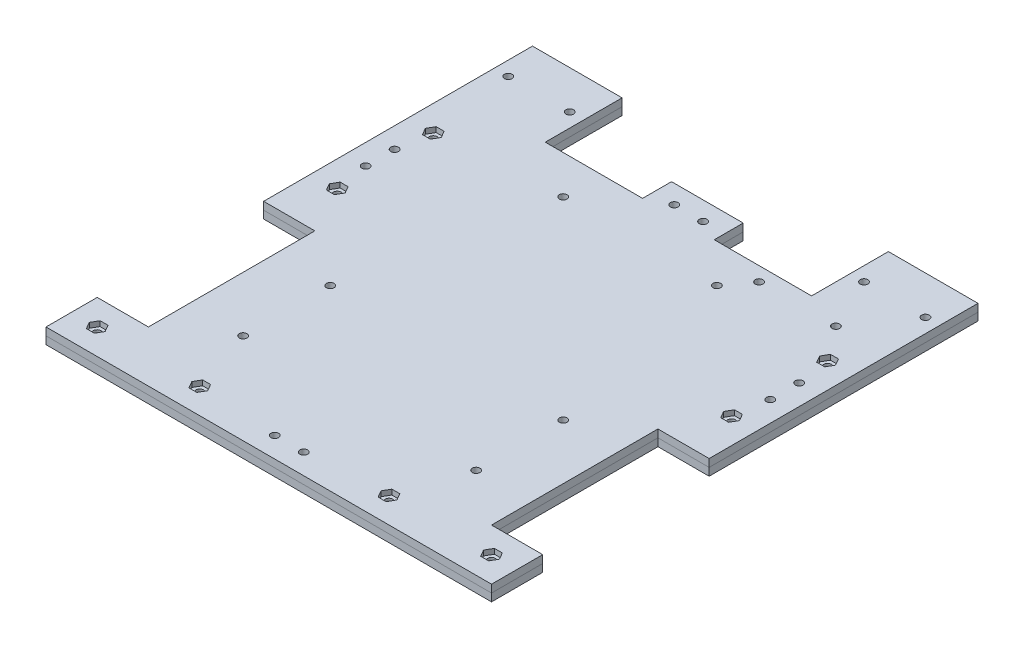
SolidWorks part; units mm, degrees
ref_plane "Alzado" through (0, 0, 0) normal (0, 0, 1) x (1, 0, 0)
ref_plane "Planta" through (0, 0, 0) normal (0, 1, 0) x (1, 0, 0)
ref_plane "Vista lateral" through (0, 0, 0) normal (1, 0, 0) x (0, 0, -1)
sketch "Croquis1" plane through (0, 0, 0) normal (0, 1, 0) x (1, 0, 0)
  line L0 (87, -80) -> (87, -60)
  line L1 (-87, 80) -> (87, 80)
  line L2 (-87, 80) -> (-87, -80)
  line L3 (-87, -80) -> (87, -80)
  line L4 (87, 80) -> (87, -80)
  line L5 (-87, 80) -> (87, -80) construction
  line L6 (-87, -80) -> (87, 80) construction
  line L7 (87, -60) -> (67, -60)
  line L8 (67, -60) -> (67, 5)
  line L9 (67, 5) -> (87, 5)
  line L10 (87, 80) -> (87, 110)
  line L11 (87, 110) -> (52, 110)
  line L12 (52, 110) -> (52, 80)
  line L13 (0, 0) -> (0, -80) construction
  line L14 (-87, -60) -> (-67, -60)
  line L15 (-67, -60) -> (-67, 5)
  line L16 (-67, 5) -> (-87, 5)
  line L17 (-87, 80) -> (-87, 110)
  line L18 (-87, 110) -> (-52, 110)
  line L19 (-52, 110) -> (-52, 80)
  point P0 (0, 0)
  dimension "D1" = 160
  dimension "D2" = 174
  dimension "D3" = 20
  dimension "D4" = 20
  dimension "D5" = 65
  dimension "D6" = 30
  dimension "D7" = 35
extrude "Saliente-Extruir1" add sketch "Croquis1" along normal blind 7 contours L16 L15 L14 L2 L3 L0 L7 L8 L9 L4 L1 | L11 L12 L1 L10 | L19 L18 L17 L1
sketch "Croquis3" plane through (0, 7, 0) normal (0, 1, 0) x (1, 0, 0)
  line L0 (-87, -60) -> (-87, -80) construction
  line L1 (-87, -60) -> (-67, -60) construction
  line L2 (-87, -80) -> (87, -80) construction
  line L3 (-87, -60) -> (-87, -80) construction
  line L4 (-87, -80) -> (-87, -60) construction
  line L5 (-87, -60) -> (-67, -60) construction
  line L6 (-67, -60) -> (-77, -60) construction
  line L7 (-77, -60) -> (-87, -60) construction
  line L8 (-87, -60) -> (-87, -80) construction
  line L9 (-87, -80) -> (-87, -70) construction
  line L10 (-87, 5) -> (-67, 5) construction
  line L11 (-80.1, -70) -> (-78.55, -72.6847)
  line L12 (-78.55, -72.6847) -> (-75.45, -72.6847)
  line L13 (-75.45, -72.6847) -> (-73.9, -70)
  line L14 (-73.9, -70) -> (-75.45, -67.3153)
  line L15 (-75.45, -67.3153) -> (-78.55, -67.3153)
  line L16 (-78.55, -67.3153) -> (-80.1, -70)
  line L17 (-87, 110) -> (-87, 5) construction
  line L18 (-67, 5) -> (-87, 5) construction
  line L19 (-67, -60) -> (-67, 5) construction
  line L20 (-67, 5) -> (-77, 5) construction
  line L21 (-52, 110) -> (-52, 80) construction
  line L22 (-52, 110) -> (-52, 80) construction
  line L23 (-52, 80) -> (-87, 80) construction
  line L24 (-87, 80) -> (-69.5, 80) construction
  line L25 (-67, 5) -> (-67, 80) construction
  line L26 (-67, 80) -> (-77, 80) construction
  line L27 (-77, 80) -> (-77, 5) construction
  line L28 (-77, 5) -> (-77, 80) construction
  line L29 (-77, 80) -> (-77, 42.5) construction
  line L30 (-77, 42.5) -> (-77, 5) construction
  line L31 (-77, 5) -> (-77, 23.75) construction
  line L32 (-77, 23.75) -> (-77, 42.5) construction
  line L33 (-77, 42.5) -> (-77, 61.25) construction
  line L34 (0, 0) -> (0, -80) construction
  line L35 (-80.1, 61.25) -> (-78.55, 58.5653)
  line L36 (-78.55, 58.5653) -> (-75.45, 58.5653)
  line L37 (-75.45, 58.5653) -> (-73.9, 61.25)
  line L38 (-73.9, 61.25) -> (-75.45, 63.9347)
  line L39 (-75.45, 63.9347) -> (-78.55, 63.9347)
  line L40 (-78.55, 63.9347) -> (-80.1, 61.25)
  line L41 (-73.9, 23.75) -> (-75.45, 26.4347)
  line L42 (-75.45, 26.4347) -> (-78.55, 26.4347)
  line L43 (-78.55, 26.4347) -> (-80.1, 23.75)
  line L44 (-80.1, 23.75) -> (-78.55, 21.0653)
  line L45 (-78.55, 21.0653) -> (-75.45, 21.0653)
  line L46 (-75.45, 21.0653) -> (-73.9, 23.75)
  line L47 (78.55, 63.9347) -> (80.1, 61.25)
  line L48 (75.45, 63.9347) -> (78.55, 63.9347)
  line L49 (73.9, 61.25) -> (75.45, 63.9347)
  line L50 (75.45, 58.5653) -> (73.9, 61.25)
  line L51 (78.55, 58.5653) -> (75.45, 58.5653)
  line L52 (80.1, 61.25) -> (78.55, 58.5653)
  line L53 (75.45, 21.0653) -> (73.9, 23.75)
  line L54 (78.55, 21.0653) -> (75.45, 21.0653)
  line L55 (80.1, 23.75) -> (78.55, 21.0653)
  line L56 (78.55, 26.4347) -> (80.1, 23.75)
  line L57 (75.45, 26.4347) -> (78.55, 26.4347)
  line L58 (73.9, 23.75) -> (75.45, 26.4347)
  line L59 (78.55, -67.3153) -> (80.1, -70)
  line L60 (75.45, -67.3153) -> (78.55, -67.3153)
  line L61 (73.9, -70) -> (75.45, -67.3153)
  line L62 (75.45, -72.6847) -> (73.9, -70)
  line L63 (78.55, -72.6847) -> (75.45, -72.6847)
  line L64 (80.1, -70) -> (78.55, -72.6847)
  circle A0 centre (-77, -70) radius 3.1 construction
  circle A1 centre (-77, 61.25) radius 3.1 construction
  circle A2 centre (-77, 23.75) radius 3.1 construction
extrude "Cortar-Extruir1" cut sketch "Croquis3" against normal blind 2
sketch "Croquis4" plane through (0, 0, 0) normal (0, -1, 0) x (1, 0, 0)
  line L0 (-78.55, 67.3153) -> (-80.1, 70) construction
  line L1 (-80.1, 70) -> (-78.55, 72.6847) construction
  line L2 (-78.55, 72.6847) -> (-75.45, 72.6847) construction
  line L3 (-75.45, 72.6847) -> (-73.9, 70) construction
  line L4 (-73.9, 70) -> (-75.45, 67.3153) construction
  line L5 (-75.45, 67.3153) -> (-78.55, 67.3153) construction
  line L6 (-75.45, -21.0653) -> (-73.9, -23.75) construction
  line L7 (-73.9, -23.75) -> (-75.45, -26.4347) construction
  line L8 (-75.45, -26.4347) -> (-78.55, -26.4347) construction
  line L9 (-78.55, -26.4347) -> (-80.1, -23.75) construction
  line L10 (-80.1, -23.75) -> (-78.55, -21.0653) construction
  line L11 (-78.55, -21.0653) -> (-75.45, -21.0653) construction
  line L12 (-78.55, -63.9347) -> (-80.1, -61.25) construction
  line L13 (-80.1, -61.25) -> (-78.55, -58.5653) construction
  line L14 (-78.55, -58.5653) -> (-75.45, -58.5653) construction
  line L15 (-75.45, -58.5653) -> (-73.9, -61.25) construction
  line L16 (-73.9, -61.25) -> (-75.45, -63.9347) construction
  line L17 (-75.45, -63.9347) -> (-78.55, -63.9347) construction
  line L18 (78.55, -63.9347) -> (75.45, -63.9347) construction
  line L19 (75.45, -63.9347) -> (73.9, -61.25) construction
  line L20 (73.9, -61.25) -> (75.45, -58.5653) construction
  line L21 (75.45, -58.5653) -> (78.55, -58.5653) construction
  line L22 (78.55, -58.5653) -> (80.1, -61.25) construction
  line L23 (80.1, -61.25) -> (78.55, -63.9347) construction
  line L24 (75.45, -21.0653) -> (78.55, -21.0653) construction
  line L25 (78.55, -21.0653) -> (80.1, -23.75) construction
  line L26 (80.1, -23.75) -> (78.55, -26.4347) construction
  line L27 (78.55, -26.4347) -> (75.45, -26.4347) construction
  line L28 (75.45, -26.4347) -> (73.9, -23.75) construction
  line L29 (73.9, -23.75) -> (75.45, -21.0653) construction
  line L30 (78.55, 67.3153) -> (75.45, 67.3153) construction
  line L31 (75.45, 67.3153) -> (73.9, 70) construction
  line L32 (73.9, 70) -> (75.45, 72.6847) construction
  line L33 (75.45, 72.6847) -> (78.55, 72.6847) construction
  line L34 (78.55, 72.6847) -> (80.1, 70) construction
  line L35 (80.1, 70) -> (78.55, 67.3153) construction
  line L36 (-78.55, 67.3153) -> (-80.1, 70)
  line L37 (-80.1, 70) -> (-78.55, 72.6847)
  line L38 (-78.55, 72.6847) -> (-75.45, 72.6847)
  line L39 (-75.45, 72.6847) -> (-73.9, 70)
  line L40 (-73.9, 70) -> (-75.45, 67.3153)
  line L41 (-75.45, 67.3153) -> (-78.55, 67.3153)
  line L42 (-75.45, -21.0653) -> (-73.9, -23.75)
  line L43 (-73.9, -23.75) -> (-75.45, -26.4347)
  line L44 (-75.45, -26.4347) -> (-78.55, -26.4347)
  line L45 (-78.55, -26.4347) -> (-80.1, -23.75)
  line L46 (-80.1, -23.75) -> (-78.55, -21.0653)
  line L47 (-78.55, -21.0653) -> (-75.45, -21.0653)
  line L48 (-78.55, -63.9347) -> (-80.1, -61.25)
  line L49 (-80.1, -61.25) -> (-78.55, -58.5653)
  line L50 (-78.55, -58.5653) -> (-75.45, -58.5653)
  line L51 (-75.45, -58.5653) -> (-73.9, -61.25)
  line L52 (-73.9, -61.25) -> (-75.45, -63.9347)
  line L53 (-75.45, -63.9347) -> (-78.55, -63.9347)
  line L54 (78.55, -63.9347) -> (75.45, -63.9347)
  line L55 (75.45, -63.9347) -> (73.9, -61.25)
  line L56 (73.9, -61.25) -> (75.45, -58.5653)
  line L57 (75.45, -58.5653) -> (78.55, -58.5653)
  line L58 (78.55, -58.5653) -> (80.1, -61.25)
  line L59 (80.1, -61.25) -> (78.55, -63.9347)
  line L60 (75.45, -21.0653) -> (78.55, -21.0653)
  line L61 (78.55, -21.0653) -> (80.1, -23.75)
  line L62 (80.1, -23.75) -> (78.55, -26.4347)
  line L63 (78.55, -26.4347) -> (75.45, -26.4347)
  line L64 (75.45, -26.4347) -> (73.9, -23.75)
  line L65 (73.9, -23.75) -> (75.45, -21.0653)
  line L66 (78.55, 67.3153) -> (75.45, 67.3153)
  line L67 (75.45, 67.3153) -> (73.9, 70)
  line L68 (73.9, 70) -> (75.45, 72.6847)
  line L69 (75.45, 72.6847) -> (78.55, 72.6847)
  line L70 (78.55, 72.6847) -> (80.1, 70)
  line L71 (80.1, 70) -> (78.55, 67.3153)
  line L72 (-73.9, 70) -> (-80.1, 70) construction
  line L73 (-80.1, 70) -> (-77, 70) construction
  line L74 (-77, 70) -> (80.1, 70) construction
  line L75 (73.9, 70) -> (80.1, 70) construction
  line L76 (77, 70) -> (73.9, 70) construction
  line L77 (73.9, 70) -> (-73.9, 70) construction
  line L78 (-73.9, 70) -> (73.9, 70) construction
  line L79 (0, 0) -> (0, 70) construction
  line L80 (0, 70) -> (73.9, 70) construction
  line L81 (0, 70) -> (-73.9, 70) construction
  line L82 (-36.95, 70) -> (0, 70) construction
  line L83 (0, 70) -> (73.9, 70) construction
  line L84 (36.95, 70) -> (73.9, 70) construction
  line L92 (40.05, 70) -> (38.5, 72.6847)
  line L93 (38.5, 72.6847) -> (35.4, 72.6847)
  line L94 (35.4, 72.6847) -> (33.85, 70)
  line L95 (33.85, 70) -> (35.4, 67.3153)
  line L96 (35.4, 67.3153) -> (38.5, 67.3153)
  line L97 (38.5, 67.3153) -> (40.05, 70)
  line L98 (-33.85, 70) -> (-35.4, 72.6847)
  line L99 (-35.4, 72.6847) -> (-38.5, 72.6847)
  line L100 (-38.5, 72.6847) -> (-40.05, 70)
  line L101 (-40.05, 70) -> (-38.5, 67.3153)
  line L102 (-38.5, 67.3153) -> (-35.4, 67.3153)
  line L103 (-35.4, 67.3153) -> (-33.85, 70)
  circle A0 centre (-36.95, 70) radius 3.1 construction
  circle A1 centre (36.95, 70) radius 3.1 construction
extrude "Cortar-Extruir2" cut sketch "Croquis4" against normal blind 2
sketch "Croquis5" plane through (0, 7, 0) normal (0, 1, 0) x (1, 0, 0)
  line L0 (78.55, -67.3153) -> (75.45, -67.3153) construction
  line L1 (75.45, -67.3153) -> (73.9, -70) construction
  line L2 (73.9, -70) -> (75.45, -72.6847) construction
  line L3 (75.45, -72.6847) -> (78.55, -72.6847) construction
  line L4 (78.55, -72.6847) -> (80.1, -70) construction
  line L5 (80.1, -70) -> (78.55, -67.3153) construction
  line L6 (-78.55, -67.3153) -> (-80.1, -70) construction
  line L7 (-80.1, -70) -> (-78.55, -72.6847) construction
  line L8 (-78.55, -72.6847) -> (-75.45, -72.6847) construction
  line L9 (-75.45, -72.6847) -> (-73.9, -70) construction
  line L10 (-73.9, -70) -> (-75.45, -67.3153) construction
  line L11 (-75.45, -67.3153) -> (-78.55, -67.3153) construction
  line L12 (-75.45, 21.0653) -> (-73.9, 23.75) construction
  line L13 (-73.9, 23.75) -> (-75.45, 26.4347) construction
  line L14 (-75.45, 26.4347) -> (-78.55, 26.4347) construction
  line L15 (-78.55, 26.4347) -> (-80.1, 23.75) construction
  line L16 (-80.1, 23.75) -> (-78.55, 21.0653) construction
  line L17 (-78.55, 21.0653) -> (-75.45, 21.0653) construction
  line L18 (75.45, 21.0653) -> (78.55, 21.0653) construction
  line L19 (78.55, 21.0653) -> (80.1, 23.75) construction
  line L20 (80.1, 23.75) -> (78.55, 26.4347) construction
  line L21 (78.55, 26.4347) -> (75.45, 26.4347) construction
  line L22 (75.45, 26.4347) -> (73.9, 23.75) construction
  line L23 (73.9, 23.75) -> (75.45, 21.0653) construction
  line L24 (78.55, 63.9347) -> (75.45, 63.9347) construction
  line L25 (75.45, 63.9347) -> (73.9, 61.25) construction
  line L26 (73.9, 61.25) -> (75.45, 58.5653) construction
  line L27 (75.45, 58.5653) -> (78.55, 58.5653) construction
  line L28 (78.55, 58.5653) -> (80.1, 61.25) construction
  line L29 (80.1, 61.25) -> (78.55, 63.9347) construction
  line L30 (-78.55, 63.9347) -> (-80.1, 61.25) construction
  line L31 (-80.1, 61.25) -> (-78.55, 58.5653) construction
  line L32 (-78.55, 58.5653) -> (-75.45, 58.5653) construction
  line L33 (-75.45, 58.5653) -> (-73.9, 61.25) construction
  line L34 (-73.9, 61.25) -> (-75.45, 63.9347) construction
  line L35 (-75.45, 63.9347) -> (-78.55, 63.9347) construction
  line L36 (78.55, -67.3153) -> (75.45, -67.3153)
  line L37 (75.45, -67.3153) -> (73.9, -70)
  line L38 (73.9, -70) -> (75.45, -72.6847)
  line L39 (75.45, -72.6847) -> (78.55, -72.6847)
  line L40 (78.55, -72.6847) -> (80.1, -70)
  line L41 (80.1, -70) -> (78.55, -67.3153)
  line L42 (-78.55, -67.3153) -> (-80.1, -70)
  line L43 (-80.1, -70) -> (-78.55, -72.6847)
  line L44 (-78.55, -72.6847) -> (-75.45, -72.6847)
  line L45 (-75.45, -72.6847) -> (-73.9, -70)
  line L46 (-73.9, -70) -> (-75.45, -67.3153)
  line L47 (-75.45, -67.3153) -> (-78.55, -67.3153)
  line L48 (-75.45, 21.0653) -> (-73.9, 23.75)
  line L49 (-73.9, 23.75) -> (-75.45, 26.4347)
  line L50 (-75.45, 26.4347) -> (-78.55, 26.4347)
  line L51 (-78.55, 26.4347) -> (-80.1, 23.75)
  line L52 (-80.1, 23.75) -> (-78.55, 21.0653)
  line L53 (-78.55, 21.0653) -> (-75.45, 21.0653)
  line L54 (75.45, 21.0653) -> (78.55, 21.0653)
  line L55 (78.55, 21.0653) -> (80.1, 23.75)
  line L56 (80.1, 23.75) -> (78.55, 26.4347)
  line L57 (78.55, 26.4347) -> (75.45, 26.4347)
  line L58 (75.45, 26.4347) -> (73.9, 23.75)
  line L59 (73.9, 23.75) -> (75.45, 21.0653)
  line L60 (78.55, 63.9347) -> (75.45, 63.9347)
  line L61 (75.45, 63.9347) -> (73.9, 61.25)
  line L62 (73.9, 61.25) -> (75.45, 58.5653)
  line L63 (75.45, 58.5653) -> (78.55, 58.5653)
  line L64 (78.55, 58.5653) -> (80.1, 61.25)
  line L65 (80.1, 61.25) -> (78.55, 63.9347)
  line L66 (-78.55, 63.9347) -> (-80.1, 61.25)
  line L67 (-80.1, 61.25) -> (-78.55, 58.5653)
  line L68 (-78.55, 58.5653) -> (-75.45, 58.5653)
  line L69 (-75.45, 58.5653) -> (-73.9, 61.25)
  line L70 (-73.9, 61.25) -> (-75.45, 63.9347)
  line L71 (-75.45, 63.9347) -> (-78.55, 63.9347)
  line L72 (-77, 58.5653) -> (-77, 61.25) construction
  line L73 (-77, 21.0653) -> (-77, 23.75) construction
  line L74 (-77, -72.6847) -> (-77, -70) construction
  line L75 (0, 0) -> (0, -80) construction
  line L76 (-87, -80) -> (87, -80) construction
  circle A0 centre (-77, -70) radius 1.5
  circle A1 centre (-77, 23.75) radius 1.5
  circle A2 centre (-77, 61.25) radius 1.5
  circle A3 centre (77, -70) radius 1.5
  circle A4 centre (77, 23.75) radius 1.5
  circle A5 centre (77, 61.25) radius 1.5
  dimension "D1" = 3
  dimension "D2" = 3
  dimension "D3" = 3
extrude "Cortar-Extruir5" cut sketch "Croquis5" against normal blind 12 contours A4 | A5 | A2 | A1 | A0 | A3
sketch "Croquis7" plane through (0, 7, 0) normal (0, 1, 0) x (1, 0, 0)
  line L0 (38.5, -67.3153) -> (40.05, -70) construction
  line L1 (40.05, -70) -> (38.5, -72.6847) construction
  line L2 (38.5, -72.6847) -> (35.4, -72.6847) construction
  line L3 (35.4, -72.6847) -> (33.85, -70) construction
  line L4 (33.85, -70) -> (35.4, -67.3153) construction
  line L5 (35.4, -67.3153) -> (38.5, -67.3153) construction
  line L6 (-35.4, -67.3153) -> (-33.85, -70) construction
  line L7 (-33.85, -70) -> (-35.4, -72.6847) construction
  line L8 (-35.4, -72.6847) -> (-38.5, -72.6847) construction
  line L9 (-38.5, -72.6847) -> (-40.05, -70) construction
  line L10 (-40.05, -70) -> (-38.5, -67.3153) construction
  line L11 (-38.5, -67.3153) -> (-35.4, -67.3153) construction
  line L12 (38.5, -67.3153) -> (40.05, -70)
  line L13 (40.05, -70) -> (38.5, -72.6847)
  line L14 (38.5, -72.6847) -> (35.4, -72.6847)
  line L15 (35.4, -72.6847) -> (33.85, -70)
  line L16 (-87, 5) -> (-67, 5)
  line L17 (-67, 5) -> (-67, -60)
  line L18 (-67, -60) -> (-87, -60)
  line L19 (-87, -60) -> (-87, -80)
  line L20 (-87, -80) -> (87, -80)
  line L21 (87, -80) -> (87, -60)
  line L22 (87, -60) -> (67, -60)
  line L23 (67, -60) -> (67, 5)
  line L24 (67, 5) -> (87, 5)
  line L25 (87, 5) -> (87, 110)
  line L26 (87, 110) -> (52, 110)
  line L27 (52, 110) -> (52, 80)
  line L28 (52, 80) -> (-52, 80)
  line L29 (-52, 80) -> (-52, 110)
  line L30 (-52, 110) -> (-87, 110)
  line L31 (-87, 110) -> (-87, 5)
  line L32 (-87, 5) -> (-67, 5)
  line L33 (-67, 5) -> (-67, -60)
  line L34 (-67, -60) -> (-87, -60)
  line L35 (-87, -60) -> (-87, -80)
  line L36 (-87, -80) -> (87, -80)
  line L37 (87, -80) -> (87, -60)
  line L38 (87, -60) -> (67, -60)
  line L39 (67, -60) -> (67, 5)
  line L40 (67, 5) -> (87, 5)
  line L41 (87, 5) -> (87, 110)
  line L42 (87, 110) -> (52, 110)
  line L43 (52, 110) -> (52, 80)
  line L44 (52, 80) -> (-52, 80)
  line L45 (-52, 80) -> (-52, 110)
  line L46 (-52, 110) -> (-87, 110)
  line L47 (-87, 110) -> (-87, 5)
  line L48 (33.85, -70) -> (35.4, -67.3153)
  line L49 (35.4, -67.3153) -> (38.5, -67.3153)
  line L50 (-35.4, -67.3153) -> (-33.85, -70)
  line L51 (-33.85, -70) -> (-35.4, -72.6847)
  line L52 (-35.4, -72.6847) -> (-38.5, -72.6847)
  line L53 (-38.5, -72.6847) -> (-40.05, -70)
  line L54 (-40.05, -70) -> (-38.5, -67.3153)
  line L55 (-38.5, -67.3153) -> (-35.4, -67.3153)
  dimension "D1" = 0
extrude "Cortar-Extruir6" cut sketch "Croquis7" against normal blind 2 contours L55 L54 L53 L52 L51 L50 | L49 L48 L15 L14 L13 L12
sketch "Croquis8" plane through (0, 2, 0) normal (0, -1, 0) x (1, 0, 0)
  line L0 (-33.85, 70) -> (-40.05, 70) construction
  line L1 (-40.05, 70) -> (-38.5, 67.3153) construction
  line L2 (-40.05, 70) -> (-38.5, 67.3153) construction
  line L3 (-40.05, 70) -> (-36.95, 70) construction
  line L4 (40.05, 70) -> (33.85, 70) construction
  line L5 (33.85, 70) -> (36.95, 70) construction
  circle A0 centre (36.95, 70) radius 1.5
  circle A1 centre (-36.95, 70) radius 1.5
  dimension "D1" = 3
  dimension "D2" = 3
extrude "Cortar-Extruir7" cut sketch "Croquis8" against normal blind 5
sketch "Croquis9" plane through (0, 7, 0) normal (0, 1, 0) x (1, 0, 0)
  line L0 (0, 80) -> (0, 87.0202) construction
  line L1 (-52, 80) -> (52, 80) construction
sketch "Croquis10" plane through (0, 0, 0) normal (0, -1, 0) x (1, 0, 0)
  line L0 (-69.4687, -95) -> (-57.4687, -95)
  line L1 (-69.4687, -95) -> (-81.4687, -95)
  line L2 (0, -87.0202) -> (0, -80) construction
  circle A0 centre (-81.4687, -95) radius 1.5
  circle A1 centre (-57.4687, -95) radius 1.5
  circle A2 centre (57.4687, -95) radius 1.5
  circle A3 centre (81.4687, -95) radius 1.5
  dimension "D3" = 3
  dimension "D4" = 3
  dimension "D1" = 12
  dimension "D2" = 12
extrude "Cortar-Extruir9" cut sketch "Croquis10" against normal blind 24
sketch "Croquis11" plane through (0, 0, 0) normal (0, -1, 0) x (-1, 0, 0)
  line L0 (0, 65) -> (30, 65) construction
  line L1 (0, 87.0202) -> (0, 80) construction
  circle A0 centre (30, 65) radius 1.5
  circle A1 centre (-30, 65) radius 1.5
  dimension "D1" = 3
extrude "Cortar-Extruir10" cut sketch "Croquis11" against normal blind 24 contours A0 | A1
sketch "Croquis12" plane through (0, 0, 0) normal (0, -1, 0) x (1, 0, 0)
  line L0 (-67, -5) -> (-45.5, -5)
  line L1 (-67, -5) -> (-87, -5) construction
  line L2 (-45.5, -5) -> (-45.5, 10.5)
  line L3 (-45.5, 10.5) -> (-45.5, 44.5)
  line L4 (-87, 80) -> (87, 80) construction
  line L5 (-87, 80) -> (87, 80) construction
  line L6 (87, 80) -> (87, 60) construction
  line L7 (87, 80) -> (0, 80) construction
  line L8 (0, 80) -> (0, 49.2487) construction
  circle A0 centre (-45.5, 10.5) radius 1.5
  circle A1 centre (-45.5, 44.5) radius 1.5
  circle A2 centre (45.5, 10.5) radius 1.5
  circle A3 centre (45.5, 44.5) radius 1.5
  dimension "D3" = 3
  dimension "D5" = 3
  dimension "D1" = 21.5
  dimension "D2" = 15.5
  dimension "D4" = 34
extrude "Cortar-Extruir11" cut sketch "Croquis12" against normal blind 24 contours A3 | A1 | A0 | A2
sketch "Croquis13" plane through (0, 7, 0) normal (0, 1, 0) x (1, 0, 0)
  line L0 (52, 80) -> (37, 80) construction
  line L1 (-52, 80) -> (52, 80) construction
  line L2 (52, 110) -> (52, 80) construction
  line L3 (37, 80) -> (37, 74.5) construction
  line L4 (52, 80) -> (52, 88.3429) construction
  circle A0 centre (37, 74.5) radius 1.5
  circle A1 centre (67, 74.5) radius 1.5
  dimension "D3" = 3
  dimension "D1" = 15
  dimension "D2" = 5.5
extrude "Cortar-Extruir12" cut sketch "Croquis13" against normal blind 11
sketch "Croquis14" plane through (0, 0, -80) normal (0, 0, -1) x (-1, 0, 0)
  line L0 (-14, 0) -> (14, 0)
  line L1 (52, 0) -> (-52, 0) construction
  line L2 (-14, 0) -> (-14, 7)
  line L3 (52, 7) -> (-52, 7) construction
  line L4 (-14, 7) -> (14, 7)
  line L5 (14, 7) -> (14, 0)
  point P5 (0, 0)
  dimension "D1" = 28
extrude "Saliente-Extruir2" add sketch "Croquis14" along normal blind 11.3
sketch "Croquis15" plane through (0, 7, 0) normal (0, 1, 0) x (1, 0, 0)
  line L0 (-5.65, 80) -> (5.65, 80)
  line L1 (-5.65, 80) -> (-5.65, 84)
  line L2 (5.65, 80) -> (5.65, 84)
  circle A0 centre (-5.65, 84) radius 1.5
  circle A1 centre (5.65, 84) radius 1.5
  point P3 (0, 80)
  dimension "D4" = 3
  dimension "D5" = 3
  dimension "D1" = 11.3
  dimension "D2" = 4
  dimension "D3" = 4
extrude "Cortar-Extruir13" cut sketch "Croquis15" against normal blind 11.3 contours A0 | A1
sketch "Croquis16" plane through (0, 7, 0) normal (0, 1, 0) x (1, 0, 0)
  line L0 (-77, 58.5653) -> (-77, 26.4347) construction
  line L1 (-78.55, 58.5653) -> (-75.45, 58.5653) construction
  line L2 (-75.45, 26.4347) -> (-78.55, 26.4347) construction
  line L3 (-77, 26.4347) -> (-77, 42.5) construction
  line L4 (-77, 42.5) -> (-79, 42.5) construction
  line L5 (-79, 48.15) -> (-79, 36.85)
  line L6 (0, 80) -> (0, 77.6148) construction
  circle A0 centre (-79, 48.15) radius 1.5
  circle A1 centre (-79, 36.85) radius 1.5
  circle A2 centre (79, 36.85) radius 1.5
  circle A3 centre (79, 48.15) radius 1.5
  point P11 (-79, 42.5)
  dimension "D3" = 3
  dimension "D4" = 3
  dimension "D1" = 2
  dimension "D2" = 11.3
extrude "Cortar-Extruir14" cut sketch "Croquis16" against normal blind 11.3
sketch "Croquis17" plane through (0, 7, 0) normal (0, 1, 0) x (1, 0, 0)
  line L0 (0, 80) -> (0, -80) construction
  line L1 (-87, -80) -> (87, -80) construction
  line L2 (0, -80) -> (0, -72)
  line L3 (-5.65, -72) -> (5.65, -72)
  circle A0 centre (5.65, -72) radius 1.5
  circle A1 centre (-5.65, -72) radius 1.5
  point P8 (0, -72)
  dimension "D3" = 3
  dimension "D4" = 3
  dimension "D1" = 8
  dimension "D2" = 11.3
extrude "Cortar-Extruir15" cut sketch "Croquis17" against normal blind 11.3
sketch "Croquis18" plane through (-87, 0, 0) normal (-1, 0, 0) x (0, 0, 1)
  line L0 (-110, 7) -> (-110, 0) construction
  line L1 (-110, 4) -> (-110, 3)
  line L3 (-110, 4) -> (80, 4)
  line L4 (-110, 4) -> (-110, 3)
  line L5 (-110, 3) -> (80, 3)
  line L6 (80, 4) -> (80, 3)
  point P5 (-110, 3.5)
  line M7 (-5, 0) -> (-5, 7)
  dimension "D1" = 1
extrude "Cortar-Extruir17" cut sketch "Croquis18" against normal blind 1000 contours L6 L3 L5 M7
move or copy body "Sólido-Mover/Copiar1" bodies to move or copy 122 copy no translate (0, 1, 0) parameters "D1"=0, "D2"=1, "D3"=0
